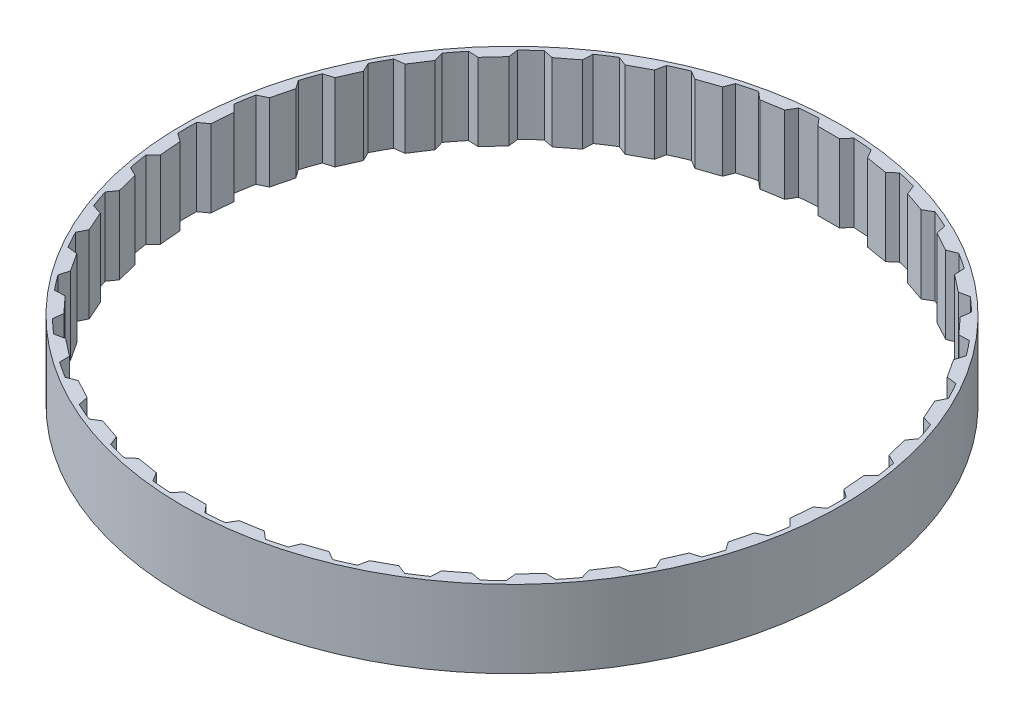
SolidWorks part; units mm, degrees
ref_plane "前视基准面" through (0, 0, 0) normal (0, 0, 1) x (1, 0, 0)
ref_plane "上视基准面" through (0, 0, 0) normal (0, 1, 0) x (1, 0, 0)
ref_plane "右视基准面" through (0, 0, 0) normal (1, 0, 0) x (0, 0, -1)
sketch "草图1" plane through (0, 0, 0) normal (0, 1, 0) x (1, 0, 0)
  line L0 (0, 0) -> (0, 42) construction
  line L1 (0, 42) -> (0, 42.6) construction
  line L2 (0, 42.6) -> (0, 56.3497) construction
  circle A0 centre (0, 0) radius 42.6
  circle A1 centre (0, 0) radius 42
  dimension "D1" = 84
  dimension "D2" = 0.6
extrude "凸台-拉伸1" add sketch "草图1" along normal blind 10
sketch "草图2" plane through (0, 10, 0) normal (0, 1, 0) x (1, 0, 0)
  line L0 (0, 0) -> (0, 85.8392) construction
  line L1 (-2.25, 41.9397) -> (-1.4, 40.9397)
  line L2 (-1.4, 40.9397) -> (1.4, 40.9397)
  line L3 (2.25, 41.9397) -> (1.4, 40.9397)
  circle A0 centre (0, 0) radius 42 construction
  circle A1 centre (0, 0) radius 42
  point P10 (0, 40.9397)
  circle M6 centre (0, 0) radius 42
  dimension "D1" = 2.8
  dimension "D2" = 1
  dimension "D3" = 4.5
extrude "凸台-拉伸2" add sketch "草图2" against normal up to surface (10 mm away) contours L2 L0 L1 M6 | L0 L2 L3 A1 up to face at (0, 0, 42.6)
pattern_circular "阵列(圆周)1" count 38 over 360 about axis through (0, 0, 0) along (0, 1, 0) of "凸台-拉伸2"
